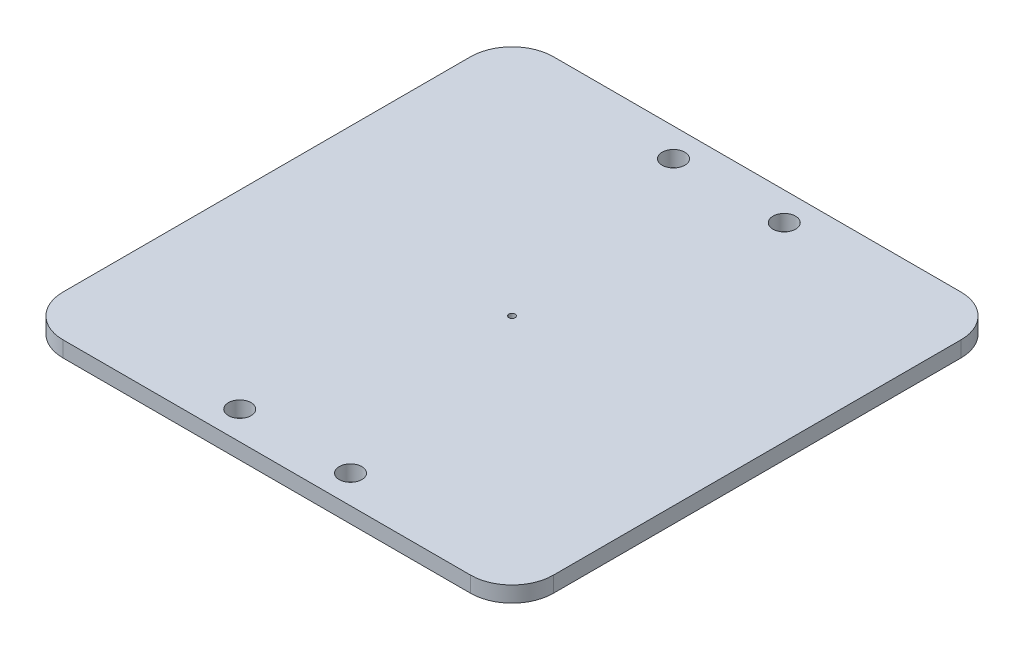
SolidWorks part; units mm, degrees
ref_plane "Front" through (0, 0, 0) normal (0, 0, 1) x (1, 0, 0)
ref_plane "Top" through (0, 0, 0) normal (0, 1, 0) x (1, 0, 0)
ref_plane "Right" through (0, 0, 0) normal (1, 0, 0) x (0, 0, -1)
sketch "Sketch1" plane through (0, 0, 0) normal (0, 1, 0) x (1, 0, 0)
  line L1 (-22.5425, 22.5425) -> (22.5425, 22.5425)
  line L2 (-22.5425, 22.5425) -> (-22.5425, -22.5425)
  line L3 (-22.5425, -22.5425) -> (22.5425, -22.5425)
  line L4 (22.5425, 22.5425) -> (22.5425, -22.5425)
  line L5 (-22.5425, 22.5425) -> (22.5425, -22.5425) construction
  line L6 (-22.5425, -22.5425) -> (22.5425, 22.5425) construction
  point P0 (0, 0)
  dimension "D1" = 45.085
  dimension "D2" = 45.085
extrude "Boss-Extrude1" add sketch "Sketch1" along normal blind 1.4478
sketch "Sketch2" plane through (0, 1.4478, 0) normal (0, 1, 0) x (1, 0, 0)
  line L1 (-5.0927, 19.939) -> (5.0927, 19.939)
  line L2 (-5.0927, 19.939) -> (-5.0927, -19.939)
  line L3 (-5.0927, -19.939) -> (5.0927, -19.939)
  line L4 (5.0927, 19.939) -> (5.0927, -19.939)
  line L5 (-5.0927, 19.939) -> (5.0927, -19.939) construction
  line L6 (-5.0927, -19.939) -> (5.0927, 19.939) construction
  circle A0 centre (-5.0927, 19.939) radius 1.0414
  circle A1 centre (5.0927, 19.939) radius 1.0414
  circle A2 centre (5.0927, -19.939) radius 1.0414
  circle A3 centre (-5.0927, -19.939) radius 1.0414
  circle A5 centre (0, 0) radius 0.2908
  point P0 (0, 0)
  dimension "D3" = 2.0828
  dimension "D4" = 2.0828
  dimension "D5" = 2.0828
  dimension "D6" = 2.0828
  dimension "D1" = 39.878
  dimension "D2" = 10.1854
extrude "Cut-Extrude1" cut sketch "Sketch2" against normal blind 3.54 contours A5 | A0 | A1 | A2 | A3
fillet "Fillet1" radius 3.81 4 edges at (-22.5425, 0.7239, -22.5425) (22.5425, 0.7239, -22.5425) (22.5425, 0.7239, 22.5425) (-22.5425, 0.7239, 22.5425)
